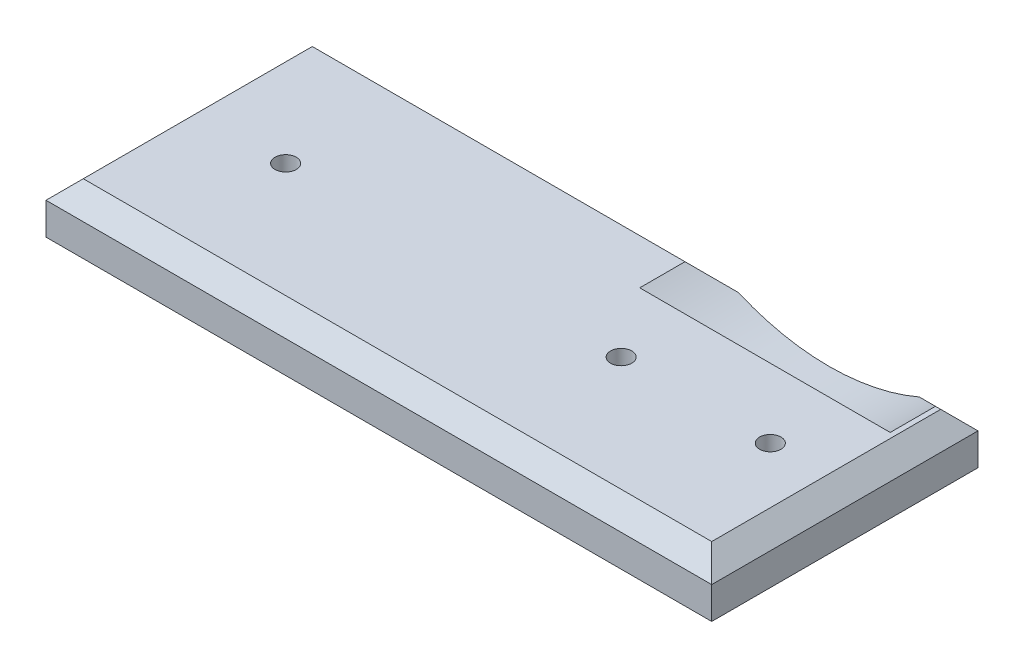
SolidWorks part; units mm, degrees
material "Oak"
ref_plane "Front Plane" through (0, 0, 0) normal (0, 0, 1) x (1, 0, 0)
ref_plane "Top Plane" through (0, 0, 0) normal (0, 1, 0) x (1, 0, 0)
ref_plane "Right Plane" through (0, 0, 0) normal (1, 0, 0) x (0, 0, -1)
sketch "Sketch1" plane through (0, 0, 0) normal (0, 1, 0) x (1, 0, 0)
  line L1 (-62.5, 25) -> (62.5, 25)
  line L2 (-62.5, 25) -> (-62.5, -25)
  line L3 (-62.5, -25) -> (62.5, -25)
  line L4 (62.5, 25) -> (62.5, -25)
  line L5 (-62.5, 25) -> (62.5, -25) construction
  line L6 (-62.5, -25) -> (62.5, 25) construction
  point P0 (0, 0)
  dimension "D1" = 125
  dimension "D2" = 50
extrude "Boss-Extrude1" add sketch "Sketch1" along normal blind 9.5
chamfer "Chamfer1" distance 3.5 angle 45 4 edges at (-62.5, 9.5, 0) (0, 9.5, -25) (62.5, 9.5, 0) (0, 9.5, 25)
sketch "Sketch3" plane through (0, 0, 0) normal (0, -1, 0) x (1, 0, 0)
  line L0 (-62.5, -25) -> (-62.5, 25) construction
  line L1 (62.5, 25) -> (62.5, -25) construction
  circle A0 centre (-42.5, 0) radius 4
  circle A1 centre (20.5, 0) radius 4
  circle A2 centre (48.5, 0) radius 4
  dimension "D1" = 8
  dimension "D3" = 42
  dimension "D2" = 20
  dimension "D4" = 14
extrude "Cut-Extrude2" cut sketch "Sketch3" against normal blind 4
sketch "Sketch4" plane through (0, 4, 0) normal (0, -1, 0) x (1, 0, 0)
  circle A0 centre (-42.5, 0) radius 2
  circle A1 centre (20.5, 0) radius 2
  circle A2 centre (48.5, 0) radius 2
extrude "Cut-Extrude3" cut sketch "Sketch4" against normal through all
sketch "Sketch6" plane through (0, 0, -25) normal (0, 0, -1) x (-1, 0, 0)
  line L0 (-62.5, 6) -> (-62.5, 0) construction
  line L1 (-59, 9.5) -> (59, 9.5) construction
  circle A0 centre (-34.5, 45.5) radius 43
  dimension "D1" = 86
  dimension "D2" = 28
  dimension "D3" = 36
extrude "Cut-Extrude4" cut sketch "Sketch6" against normal blind 12
